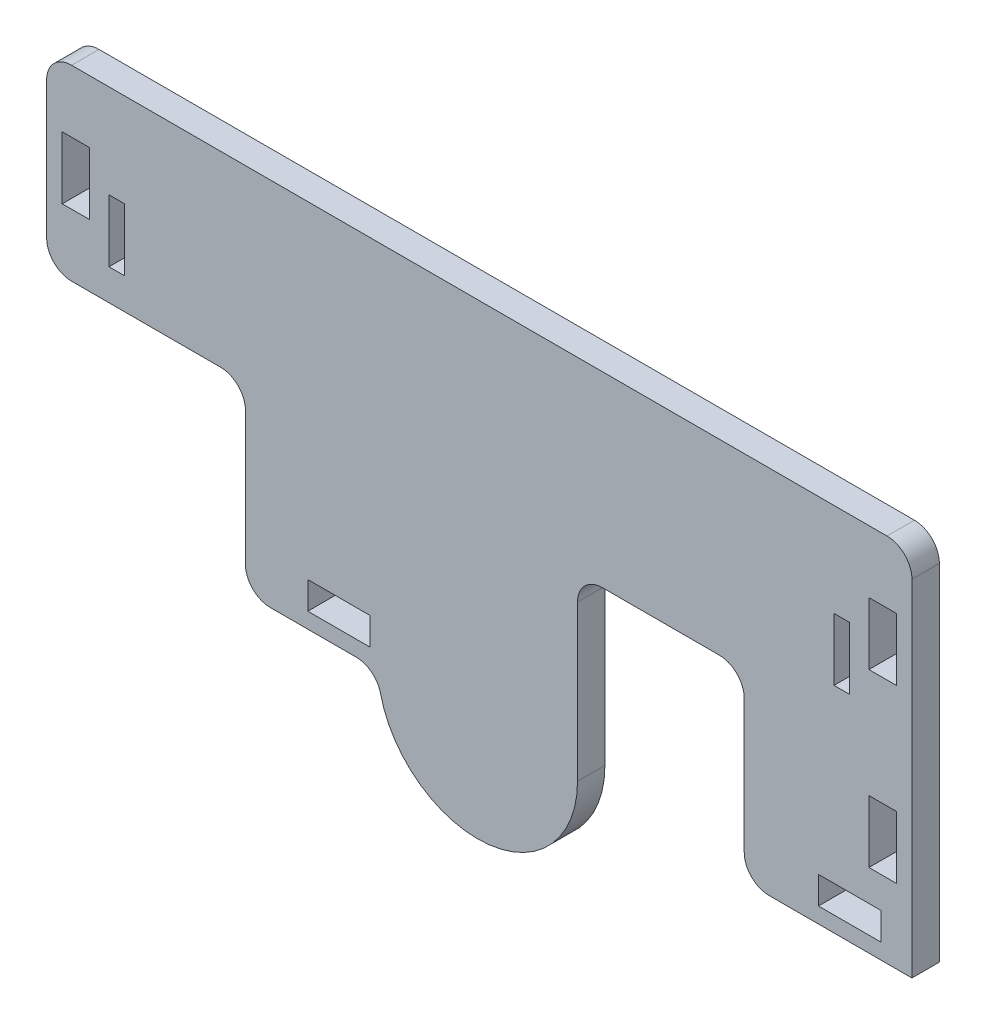
SolidWorks part; units mm, degrees
ref_plane "Front Plane" through (0, 0, 0) normal (0, 0, 1) x (1, 0, 0)
ref_plane "Top Plane" through (0, 0, 0) normal (0, 1, 0) x (1, 0, 0)
ref_plane "Right Plane" through (0, 0, 0) normal (1, 0, 0) x (0, 0, -1)
sketch "Sketch1" plane through (0, 0, 0) normal (0, 0, 1) x (1, 0, 0)
  line L0 (69.4754, -4.3815) -> (69.4754, 33.3375)
  line L1 (69.4754, 33.3375) -> (-18.6626, 33.3375)
  line L2 (-18.6626, 33.3375) -> (-18.6626, 14.2875)
  line L3 (-17.0751, 14.2875) -> (-14.2811, 14.2875) construction
  line L4 (69.4754, -4.3815) -> (52.3939, -4.3815)
  line L6 (52.3939, -4.3815) -> (52.3939, 14.2875)
  line L7 (52.3939, 14.2875) -> (35.4095, 14.2875)
  line L8 (35.4095, 14.2875) -> (35.4095, -4.0678)
  line L9 (25.4064, 33.3375) -> (25.4064, -17.5485) construction
  line L10 (65.0939, 9.525) -> (65.0939, 3.175) construction
  line L11 (50, 12.7) -> (37.3, 12.7) construction
  line L12 (-18.6626, 14.2875) -> (1.5875, 14.2875)
  line L13 (1.5875, 14.2875) -> (1.5875, -4.3815)
  line L14 (1.5875, -4.3815) -> (15.0943, -4.3815)
  line L16 (-22.0586, -14.2278) -> (72.8714, -14.2278) construction
  line L17 (0, 25.4) -> (0, 0) construction
  line L18 (-18.6626, -2.794) -> (-18.6626, 0) construction
  line L19 (69.4754, -2.794) -> (66.3004, -2.794) construction
  line L20 (69.4754, -2.794) -> (69.4754, 0) construction
  arc A0 (35.4095, -4.0678) -> (15.0943, -4.3815) centre (25.2495, -4.0678) cw
  arc A1 (-23.8239, -12.4625) -> (-20.2933, -12.4625) centre (-22.0586, -12.4625) ccw construction
  arc A2 (71.1061, -12.4625) -> (74.6367, -12.4625) centre (72.8714, -12.4625) ccw construction
  point P19 (25.4064, -14.2266)
  dimension "D1" = 10.16
  dimension "D2" = 12.7
  dimension "D3" = 1.5875
  dimension "D4" = 1.5875
  dimension "D5" = 1.5875
extrude "Boss-Extrude1" add sketch "Sketch1" along normal blind 2.794 contours L1 L2 L12 L13 L14 A0 L8 L7 L6 L4 L0
sketch "Sketch3" plane through (0, 0, 2.794) normal (0, 0, 1) x (1, 0, 0)
  line L0 (-14.2811, 20.6375) -> (-14.2811, 26.9875) construction
  line L1 (-14.2811, 26.9875) -> (-17.0751, 26.9875) construction
  line L2 (-17.0751, 26.9875) -> (-17.0751, 20.6375) construction
  line L3 (-17.0751, 20.6375) -> (-14.2811, 20.6375) construction
  line L4 (65.0939, 26.9875) -> (65.0939, 20.6375) construction
  line L5 (65.0939, 20.6375) -> (67.8879, 20.6375) construction
  line L6 (67.8879, 20.6375) -> (67.8879, 26.9875) construction
  line L7 (67.8879, 26.9875) -> (65.0939, 26.9875) construction
  line L8 (65.0939, 9.525) -> (65.0939, 3.175) construction
  line L9 (65.0939, 3.175) -> (67.8879, 3.175) construction
  line L10 (67.8879, 3.175) -> (67.8879, 9.525) construction
  line L11 (67.8879, 9.525) -> (65.0939, 9.525) construction
  line L12 (-14.2811, 20.6375) -> (-14.2811, 26.9875)
  line L13 (-14.2811, 26.9875) -> (-17.0751, 26.9875)
  line L14 (-17.0751, 26.9875) -> (-17.0751, 20.6375)
  line L15 (-17.0751, 20.6375) -> (-14.2811, 20.6375)
  line L16 (65.0939, 26.9875) -> (65.0939, 20.6375)
  line L17 (65.0939, 20.6375) -> (67.8879, 20.6375)
  line L18 (67.8879, 20.6375) -> (67.8879, 26.9875)
  line L19 (67.8879, 26.9875) -> (65.0939, 26.9875)
  line L20 (65.0939, 9.525) -> (65.0939, 3.175)
  line L21 (65.0939, 3.175) -> (67.8879, 3.175)
  line L22 (67.8879, 3.175) -> (67.8879, 9.525)
  line L23 (67.8879, 9.525) -> (65.0939, 9.525)
  line L24 (-14.2811, 23.8125) -> (-17.0751, 23.8125) construction
  line L25 (-10.7251, 23.8125) -> (-12.3126, 23.8125)
  line L26 (-10.7251, 23.8125) -> (-10.7251, 17.4625)
  line L27 (-10.7251, 17.4625) -> (-12.3126, 17.4625)
  line L28 (-12.3126, 23.8125) -> (-12.3126, 17.4625)
  line L29 (-14.2811, 17.4625) -> (-17.0751, 17.4625) construction
  line L30 (69.4754, -4.3815) -> (69.4754, 33.3375) construction
  line L31 (63.1254, 23.8125) -> (61.5379, 23.8125)
  line L32 (63.1254, 23.8125) -> (63.1254, 17.4625)
  line L33 (63.1254, 17.4625) -> (61.5379, 17.4625)
  line L34 (61.5379, 23.8125) -> (61.5379, 17.4625)
  line L35 (-18.6626, 33.3375) -> (-18.6626, 14.2875) construction
  line L36 (14.2875, 0) -> (7.9375, 0) construction
  line L37 (7.9375, 0) -> (7.9375, -2.794) construction
  line L38 (7.9375, -2.794) -> (14.2875, -2.794) construction
  line L39 (14.2875, -2.794) -> (14.2875, 0) construction
  line L40 (66.3004, 0) -> (59.9504, 0) construction
  line L41 (59.9504, 0) -> (59.9504, -2.794) construction
  line L42 (59.9504, -2.794) -> (66.3004, -2.794) construction
  line L43 (66.3004, -2.794) -> (66.3004, 0) construction
  line L44 (14.2875, 0) -> (7.9375, 0)
  line L45 (7.9375, 0) -> (7.9375, -2.794)
  line L46 (7.9375, -2.794) -> (14.2875, -2.794)
  line L47 (14.2875, -2.794) -> (14.2875, 0)
  line L48 (66.3004, 0) -> (59.9504, 0)
  line L49 (59.9504, 0) -> (59.9504, -2.794)
  line L50 (59.9504, -2.794) -> (66.3004, -2.794)
  line L51 (66.3004, -2.794) -> (66.3004, 0)
  dimension "D1" = 1.5875
  dimension "D2" = 6.35
  dimension "D3" = 1.5875
  dimension "D4" = 6.35
extrude "Cut-Extrude1" cut sketch "Sketch3" against normal through all
fillet "Fillet1" radius 2.54 9 edges at (1.5875, 14.2875, 1.397) (1.5875, -4.3815, 1.397) (52.3939, -4.3815, 1.397) (35.4095, 14.2875, 1.397) (52.3939, 14.2875, 1.397) (-18.6626, 33.3375, 1.397) (69.4754, 33.3375, 1.397) (-18.6626, 14.2875, 1.397) (15.0943, -4.3815, 1.397)
equation "\"D1@Boss-Extrude1\"=\"thick@assy.sldasm\""
